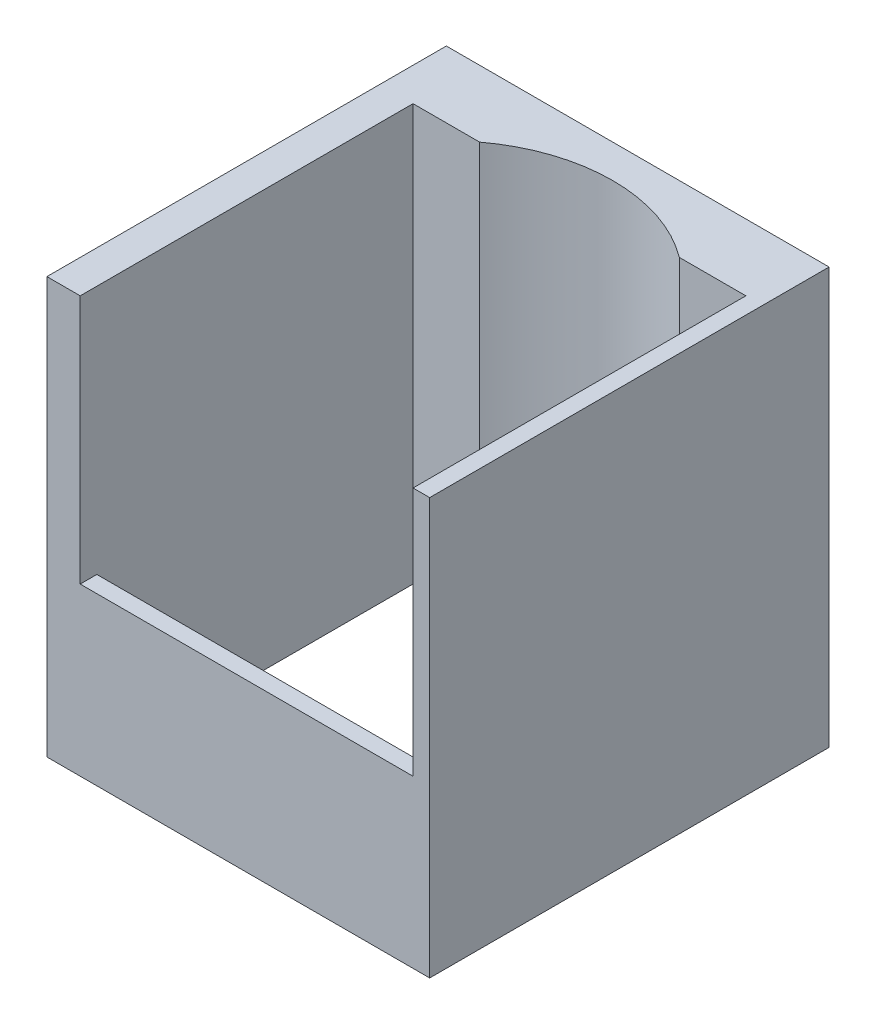
SolidWorks part; units mm, degrees
ref_plane "정면" through (0, 0, 0) normal (0, 0, 1) x (1, 0, 0)
ref_plane "윗면" through (0, 0, 0) normal (0, 1, 0) x (1, 0, 0)
ref_plane "우측면" through (0, 0, 0) normal (1, 0, 0) x (0, 0, -1)
sketch "Sketch1" plane through (0, 0, 0) normal (0, 1, 0) x (1, 0, 0)
  line L1 (0, 0) -> (670, 0)
  line L2 (0, 0) -> (0, 120)
  line L3 (0, 120) -> (670, 120)
  line L4 (670, 0) -> (670, 120)
  dimension "700" = 670
  dimension "D2" = 120
extrude "Boss-Extrude1" add sketch "Sketch1" along normal blind 530
sketch "Sketch2" plane through (0, 0, 0) normal (0, 0, 1) x (1, 0, 0)
  line L0 (0, 530) -> (0, 0) construction
  line L1 (10, 280) -> (110, 280)
  line L2 (10, 280) -> (10, 480)
  line L3 (10, 480) -> (110, 480)
  line L4 (110, 280) -> (110, 480)
  line L5 (0, 0) -> (670, 0) construction
  line L6 (120, 280) -> (120, 480)
  line L7 (120, 280) -> (220, 280)
  line L8 (220, 280) -> (220, 480)
  line L9 (120, 480) -> (220, 480)
  line L10 (230, 280) -> (230, 480)
  line L11 (230, 280) -> (330, 280)
  line L12 (330, 280) -> (330, 480)
  line L13 (230, 480) -> (330, 480)
  line L14 (340, 280) -> (340, 480)
  line L15 (340, 280) -> (440, 280)
  line L16 (440, 280) -> (440, 480)
  line L17 (340, 480) -> (440, 480)
  line L18 (450, 280) -> (450, 480)
  line L19 (450, 280) -> (550, 280)
  line L20 (550, 280) -> (550, 480)
  line L21 (450, 480) -> (550, 480)
  line L22 (560, 280) -> (560, 480)
  line L23 (560, 280) -> (660, 280)
  line L24 (660, 280) -> (660, 480)
  line L25 (560, 480) -> (660, 480)
  line L27 (10, 10) -> (660, 10)
  line L28 (10, 10) -> (10, 260)
  line L29 (10, 260) -> (660, 260)
  line L30 (660, 10) -> (660, 260)
  line L31 (0, 530) -> (670, 530) construction
  point P6 (10, 380)
  dimension "D1" = 100
  dimension "D2" = 200
  dimension "D3" = 10
  dimension "D4" = 50
  dimension "D6" = 10
  dimension "D7" = 20
  dimension "D5" = 6
extrude "Cut-Extrude1" cut sketch "Sketch2" against normal blind 100
sketch "Sketch3" plane through (0, 530, 0) normal (0, 1, 0) x (1, 0, 0)
  line L1 (670, 120) -> (0, 120) construction
  line L2 (0, 120) -> (0, 0) construction
  circle A0 centre (60, 60) radius 50
  circle A1 centre (170, 60) radius 50
  circle A2 centre (280, 60) radius 50
  circle A3 centre (390, 60) radius 50
  circle A4 centre (500, 60) radius 50
  circle A5 centre (610, 60) radius 50
  dimension "D1" = 100
  dimension "D2" = 10
  dimension "D3" = 10
  dimension "D4" = 6
extrude "Cut-Extrude2" cut sketch "Sketch3" against normal blind 260
hole_wizard "Ø12.0 (12) Diameter Hole2" positions "3DSketch1" profile "Sketch7" hole size "Ø12.0" standard "Ansi Metric"
sketch3d "3DSketch1"
  point P0 (59.7046, 270, -102.4117)
  point P2 (171.5567, 270, -102.6076)
  point P4 (280.8723, 270, -102.3969)
  point P6 (391.0687, 270, -102.7535)
  point P8 (500.7133, 270, -101.754)
  point P10 (609.5165, 270, -101.1227)
sketch "Sketch7" plane through (59.7046, 270, -102.4117) normal (1, 0, 0) x (0, 0, 1)
  line L0 (0, 0) -> (0, 33.6052)
  line L1 (0, 33.6052) -> (6, 30)
  line L2 (6, 30) -> (6, 0)
  line L5 (6, 0) -> (0, 0)
  line L10 (0, 33.6052) -> (-6, 30) construction
  line L11 (0, -6.35) -> (0, 107.95) construction
  dimension "구멍 지름" = 12
  dimension "구멍 깊이" = 30
  dimension "드릴 각도" = 118
sketch "Sketch8" plane through (0, 0, 0) normal (0, 0, 1) x (1, 0, 0)
  line L0 (660, 280) -> (660, 480) construction
  line L1 (10, 280) -> (660, 280)
  line L2 (10, 280) -> (10, 330)
  line L3 (10, 330) -> (660, 330)
  line L4 (660, 280) -> (660, 330)
  dimension "D1" = 50
extrude "Boss-Extrude2" add sketch "Sketch8" against normal blind 5
sketch "Sketch9" plane through (670, 0, 0) normal (1, 0, 0) x (0, 0, -1)
  line L0 (0, 530) -> (0, 0) construction
  line L1 (10, 10) -> (20, 10)
  line L2 (10, 10) -> (10, 260)
  line L3 (10, 260) -> (20, 260)
  line L4 (20, 10) -> (20, 260)
  line L5 (0, 0) -> (120, 0) construction
  dimension "D1" = 10
  dimension "D2" = 10
  dimension "D3" = 10
  dimension "D4" = 250
extrude "Cut-Extrude3" cut sketch "Sketch9" against normal blind 717
sketch "Sketch10" plane through (0, 10, 0) normal (0, 1, 0) x (1, 0, 0)
  line L0 (670, 120) -> (0, 120) construction
  line L1 (365, 61.9436) -> (350, 87.9243)
  line L2 (350, 87.9243) -> (320, 87.9243)
  line L3 (320, 87.9243) -> (305, 61.9436)
  line L4 (305, 61.9436) -> (320, 35.9628)
  line L5 (320, 35.9628) -> (350, 35.9628)
  line L6 (350, 35.9628) -> (365, 61.9436)
  line L7 (0, 120) -> (0, 0) construction
  circle A0 centre (335, 61.9436) radius 25.9808 construction
  dimension "D1" = 60
  dimension "D2" = 305
extrude "Cut-Extrude4" cut sketch "Sketch10" against normal blind 5
sketch "Sketch11" plane through (0, 0, -100) normal (0, 0, 1) x (1, 0, 0)
  line L0 (10, 10) -> (660, 10) construction
  line L1 (250, 10) -> (260, 10)
  line L2 (250, 10) -> (250, 110)
  line L3 (250, 110) -> (260, 110)
  line L4 (260, 10) -> (260, 110)
  line L5 (660, 10) -> (660, 260) construction
  line L6 (410, 10) -> (420, 10)
  line L7 (410, 10) -> (410, 110)
  line L8 (410, 110) -> (420, 110)
  line L9 (420, 10) -> (420, 110)
  line L10 (25, 198.4569) -> (325, 145.5588)
  line L11 (325, 145.5588) -> (325, 122.0178)
  line L12 (325, 122.0178) -> (345, 122.0178)
  line L13 (345, 122.0178) -> (345, 145.5588)
  line L14 (345, 145.5588) -> (645, 198.4569)
  line L15 (645, 198.4569) -> (25, 198.4569)
  point P18 (345, 133.7883)
  dimension "D1" = 10
  dimension "D2" = 10
  dimension "D3" = 100
  dimension "D4" = 100
  dimension "D5" = 150
  dimension "D6" = 240
  dimension "D7" = 20
  dimension "D8" = 65
  dimension "D9" = 100
  dimension "D10" = 620
  dimension "D11" = 100
extrude "Boss-Extrude3" add sketch "Sketch11" along normal blind 78 separate body
sketch "Sketch12" plane through (0, 0, -100) normal (0, 0, 1) x (1, 0, 0)
  line L0 (660, 260) -> (10, 260) construction
  line L1 (75.1986, 260) -> (95.1986, 260)
  line L2 (75.1986, 260) -> (75.1986, 230)
  line L3 (75.1986, 230) -> (95.1986, 230)
  line L4 (95.1986, 260) -> (95.1986, 230)
  line L5 (65.1986, 260) -> (65.1986, 240) construction
  line L6 (185.1986, 260) -> (185.1986, 230)
  line L7 (185.1986, 260) -> (205.1986, 260)
  line L8 (205.1986, 260) -> (205.1986, 230)
  line L9 (185.1986, 230) -> (205.1986, 230)
  line L10 (295.1986, 260) -> (295.1986, 230)
  line L11 (295.1986, 260) -> (315.1986, 260)
  line L12 (315.1986, 260) -> (315.1986, 230)
  line L13 (295.1986, 230) -> (315.1986, 230)
  line L14 (405.1986, 260) -> (405.1986, 230)
  line L15 (405.1986, 260) -> (425.1986, 260)
  line L16 (425.1986, 260) -> (425.1986, 230)
  line L17 (405.1986, 230) -> (425.1986, 230)
  line L18 (515.1986, 260) -> (515.1986, 230)
  line L19 (515.1986, 260) -> (535.1986, 260)
  line L20 (535.1986, 260) -> (535.1986, 230)
  line L21 (515.1986, 230) -> (535.1986, 230)
  line L22 (625.1986, 260) -> (625.1986, 230)
  line L23 (625.1986, 260) -> (645.1986, 260)
  line L24 (645.1986, 260) -> (645.1986, 230)
  line L25 (625.1986, 230) -> (645.1986, 230)
  dimension "D1" = 20
  dimension "D2" = 30
  dimension "D3" = 10
  dimension "D4" = 6
extrude "Cut-Extrude5" cut sketch "Sketch12" against normal blind 80
sketch "Sketch15" plane through (345, 0, 0) normal (1, 0, 0) x (0, 0, -1)
  line L0 (20, 10) -> (20, 260) construction
  line L1 (20, 121.4638) -> (50, 121.4638)
  line L2 (20, 121.4638) -> (20, 145)
  line L3 (20, 145) -> (50, 145)
  line L4 (50, 121.4638) -> (50, 145)
  line L5 (120, 530) -> (120, 0) construction
  line L6 (100, 116.0134) -> (70, 116.0134)
  line L7 (100, 116.0134) -> (100, 145)
  line L8 (100, 145) -> (70, 145)
  line L9 (70, 116.0134) -> (70, 145)
  line L10 (20, 260) -> (10, 260) construction
  dimension "D1" = 20
  dimension "D2" = 20
  dimension "D3" = 115
  dimension "D4" = 30
extrude "Cut-Extrude7" cut sketch "Sketch15" against normal blind 35
shell "Shell1" thickness 3
sketch "Sketch16" plane through (0, 122.0178, 0) normal (0, -1, 0) x (1, 0, 0)
  line L0 (345, -50) -> (325, -50) construction
  line L1 (328, -53) -> (342, -53)
  line L2 (328, -53) -> (328, -67)
  line L3 (328, -67) -> (342, -67)
  line L4 (342, -53) -> (342, -67)
  line L5 (325, -50) -> (325, -70) construction
  line L6 (345, -50) -> (345, -70) construction
  line L7 (325, -70) -> (345, -70) construction
  dimension "D1" = 3
  dimension "D2" = 3
  dimension "D3" = 3
  dimension "D4" = 3
extrude "Cut-Extrude8" cut sketch "Sketch16" against normal blind 35
sketch "Sketch17" plane through (0, 0, 0) normal (0, 0, 1) x (1, 0, 0)
  text T0 "<b>DIFF_USER</b>" font "Britannic Bold" height in points 72
extrude "Boss-Extrude4" add sketch "Sketch17" along normal blind 5
sketch "Sketch18" plane through (0, 0, 0) normal (0, 0, 1) x (1, 0, 0)
  line L0 (670, 530) -> (670, 0) construction
  line L1 (0, 0) -> (670, 0)
  line L2 (0, 0) -> (0, 280)
  line L3 (0, 280) -> (670, 280)
  line L4 (670, 0) -> (670, 280)
  dimension "D1" = 280
extrude "Cut-Extrude10" cut sketch "Sketch18" against normal blind 159
sketch "Sketch19" plane through (0, 0, 0) normal (0, 0, 1) x (1, 0, 0)
  line L0 (0, 530) -> (670, 530) construction
  line L1 (670, 280) -> (115, 280)
  line L2 (670, 280) -> (670, 530)
  line L3 (670, 530) -> (115, 530)
  line L4 (115, 280) -> (115, 530)
  line L11 (0, 530) -> (0, 280) construction
  dimension "D1" = 115
extrude "Cut-Extrude11" cut sketch "Sketch19" against normal through all both and the other way through all
sketch "Sketch20" plane through (0, 0, 0) normal (0, 0, 1) x (1, 0, 0)
  line L0 (115, 280) -> (115, 530) construction
  line L1 (0, 530) -> (115, 530)
  line L2 (0, 530) -> (0, 405)
  line L3 (0, 405) -> (115, 405)
  line L4 (115, 530) -> (115, 405)
  dimension "D1" = 125
extrude "Cut-Extrude12" cut sketch "Sketch20" against normal through all both and the other way through all
